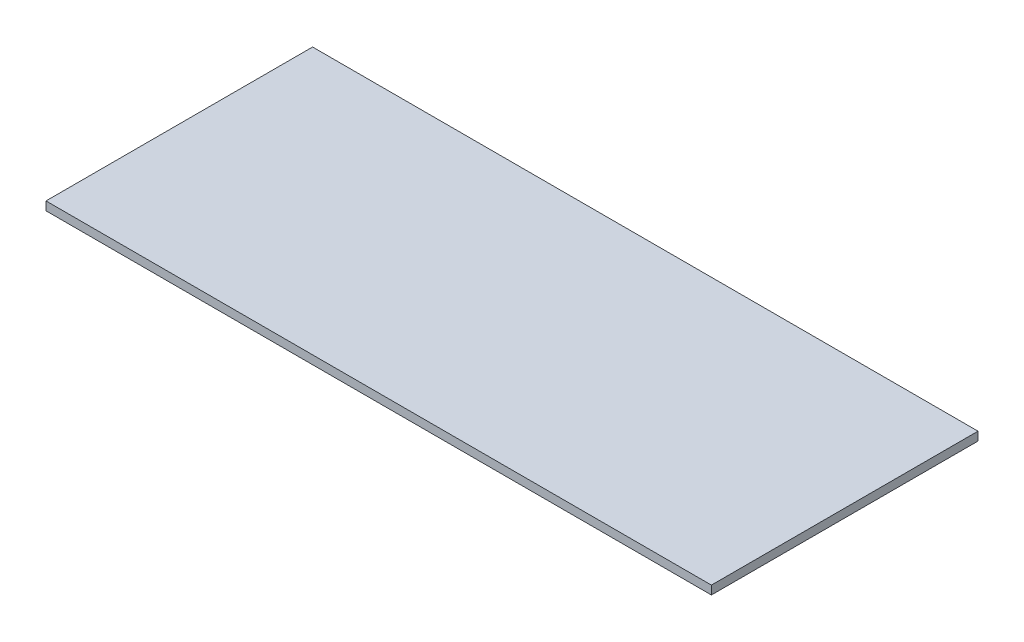
SolidWorks part; units mm, degrees
ref_plane "Front Plane" through (0, 0, 0) normal (0, 0, 1) x (1, 0, 0)
ref_plane "Top Plane" through (0, 0, 0) normal (0, 1, 0) x (1, 0, 0)
ref_plane "Right Plane" through (0, 0, 0) normal (1, 0, 0) x (0, 0, -1)
sketch "Sketch1" plane through (0, 0, 0) normal (0, 1, 0) x (1, 0, 0)
  line L1 (-196.85, 78.867) -> (196.85, 78.867)
  line L2 (-196.85, 78.867) -> (-196.85, -78.867)
  line L3 (-196.85, -78.867) -> (196.85, -78.867)
  line L4 (196.85, 78.867) -> (196.85, -78.867)
  line L5 (-196.85, 78.867) -> (196.85, -78.867) construction
  line L6 (-196.85, -78.867) -> (196.85, 78.867) construction
  point P0 (0, 0)
  dimension "D1" = 393.7
  dimension "D2" = 157.734
extrude "Boss-Extrude1" add sketch "Sketch1" along normal blind 5.08
